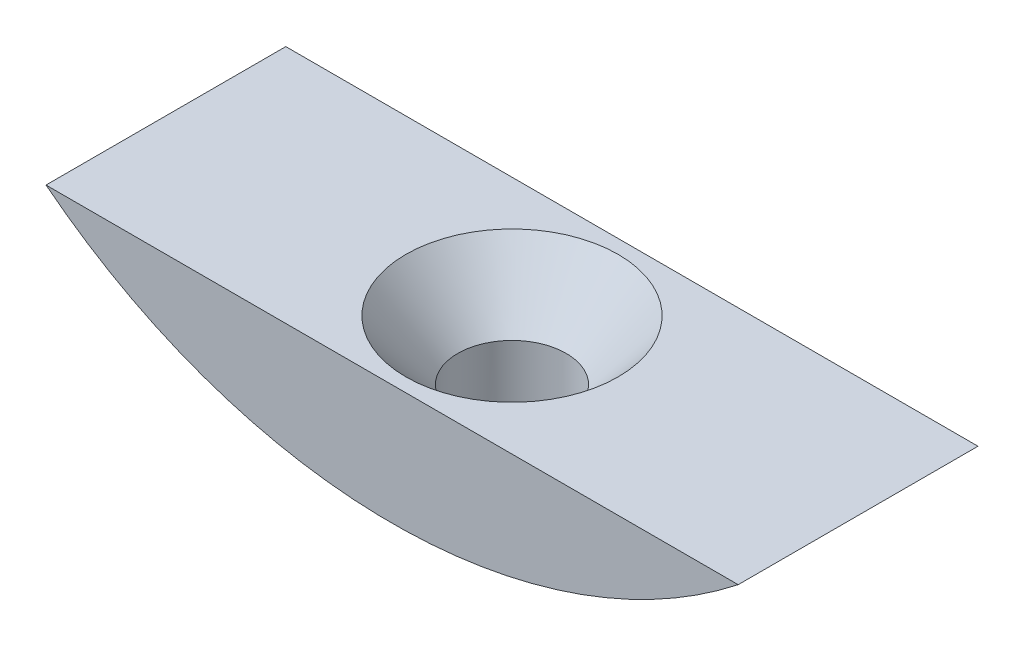
SolidWorks part; units mm, degrees
material "Plain Carbon Steel"
ref_plane "Front Plane" through (0, 0, 0) normal (0, 0, 1) x (1, 0, 0)
ref_plane "Top Plane" through (0, 0, 0) normal (0, 1, 0) x (1, 0, 0)
ref_plane "Right Plane" through (0, 0, 0) normal (1, 0, 0) x (0, 0, -1)
sketch "Sketch1" plane through (0, 0, 0) normal (0, 0, 1) x (1, 0, 0)
  line L0 (-13.7482, 0) -> (13.7482, 0)
  line L1 (0, 0) -> (0, -4.7625) construction
  arc A0 (-13.7482, 0) -> (13.7482, 0) centre (0, 17.4625) ccw
  dimension "D1" = 44.45
  dimension "D2" = 4.7625
extrude "Boss-Extrude1" add sketch "Sketch1" against normal blind 9.525
ref_plane "Plane1" through (-1.6082, 4.4186, 0) normal (-0.342, 0.9397, 0) x (0, 0, 1)
ref_plane "Plane2" through (1.6082, 4.4186, 0) normal (0.342, 0.9397, 0) x (0, 0, 1)
hole_wizard "CSK for #8 Flat Head Machine Screw1" positions "Sketch4" profile "Sketch6" countersink size "#8" standard "ANSI Inch" end condition through all
sketch "Sketch4" plane through (0, 0, 0) normal (0, 1, 0) x (1, 0, 0)
  line L0 (-13.7482, 9.525) -> (-13.7482, 0) construction
  point P0 (0, 4.7625)
  point P6 (-13.7482, 4.7625)
sketch "Sketch6" plane through (0, 0, -4.7625) normal (1, 0, 0) x (0, 0, 1)
  line L0 (0, 0) -> (0, 4.7625)
  line L1 (0, 4.7625) -> (2.1526, 4.7625)
  line L2 (2.1526, 4.7625) -> (2.1526, 2.3741)
  line L3 (2.1526, 2.3741) -> (4.2164, 0)
  line L5 (4.2164, 0) -> (0, 0)
  line L6 (-2.1527, 2.3741) -> (-4.2164, 0) construction
  line L11 (0, -6.35) -> (0, 107.95) construction
  dimension "Thru Hole Dia." = 4.3053
  dimension "Thru Hole Depth" = 4.7625
  dimension "Near C'Sink Dia." = 8.4328
  dimension "Near C'Sink Angle" = 82
